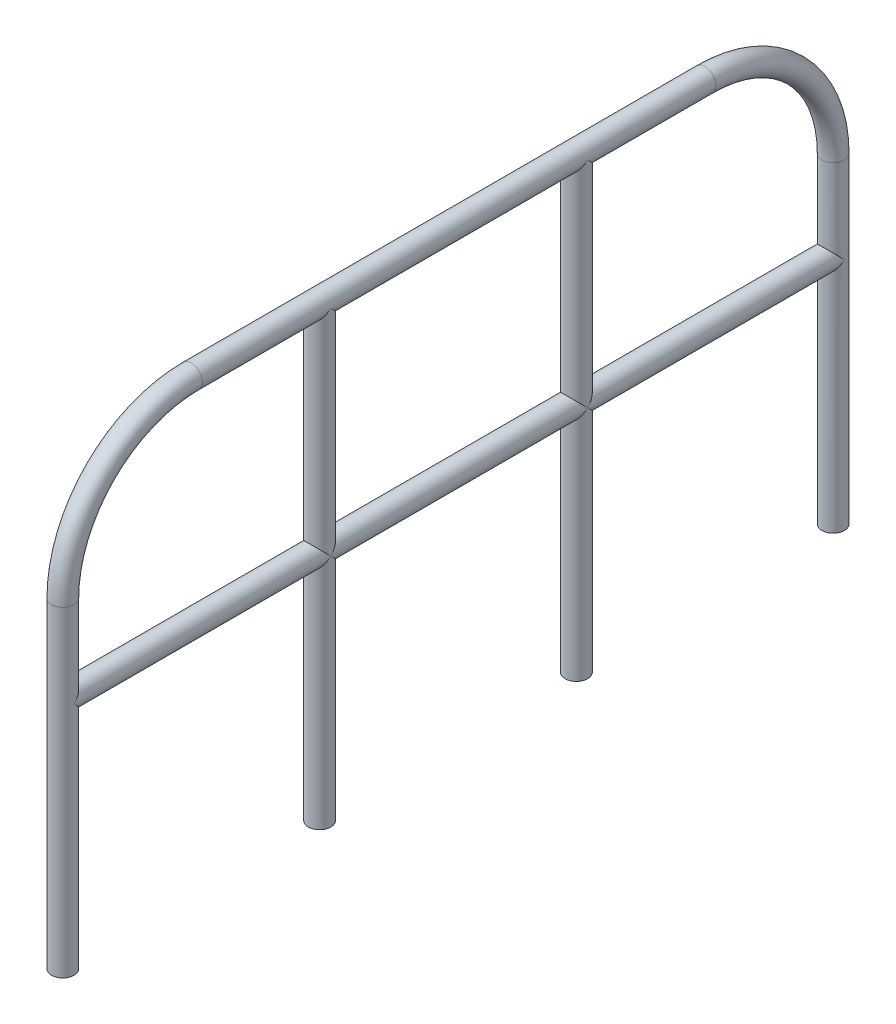
SolidWorks part; units mm, degrees
ref_plane "前视基准面" through (0, 0, 0) normal (0, 0, 1) x (1, 0, 0)
ref_plane "上视基准面" through (0, 0, 0) normal (0, 1, 0) x (1, 0, 0)
ref_plane "右视基准面" through (0, 0, 0) normal (1, 0, 0) x (0, 0, -1)
sketch "草图1" plane through (0, 0, 0) normal (1, 0, 0) x (0, 0, -1)
  line L0 (0, 0) -> (0, 1000)
  line L1 (400, 1400) -> (2000, 1400)
  line L2 (2400, 1000) -> (2400, 0)
  arc A0 (2400, 1000) -> (2000, 1400) centre (2000, 1000) ccw
  arc A1 (0, 1000) -> (400, 1400) centre (400, 1000) cw
  dimension "D1" = 400
sketch "草图2" plane through (0, 0, 0) normal (0, 1, 0) x (1, 0, 0)
  circle A0 centre (0, 0) radius 35
sweep "扫描1" add profiles "草图2" path "草图1"
sketch "草图3" plane through (0, 0, 0) normal (0, 1, 0) x (1, 0, 0)
  circle A0 centre (0, 1600) radius 35
  circle A1 centre (0, 800) radius 35
  dimension "D1" = 800
extrude "凸台-拉伸1" add sketch "草图3" along normal blind 1400
sketch "草图4" plane through (0, 0, 0) normal (0, 0, 1) x (1, 0, 0)
  circle A0 centre (0, 731.1051) radius 35
extrude "凸台-拉伸2" add sketch "草图4" against normal blind 2400
sketch "草图5" plane through (0, 0, 0) normal (0, -1, 0) x (1, 0, 0)
  line L1 (-35, 0) -> (-43.2434, 0)
  line L2 (-35, 0) -> (-35, -21.5581)
  line L3 (-35, -21.5581) -> (-43.2434, -21.5581)
  line L4 (-43.2434, 0) -> (-43.2434, -21.5581)
  circle A0 centre (0, 0) radius 35 construction
extrude "凸台-拉伸3" add sketch "草图5" against normal blind 10 separate body
